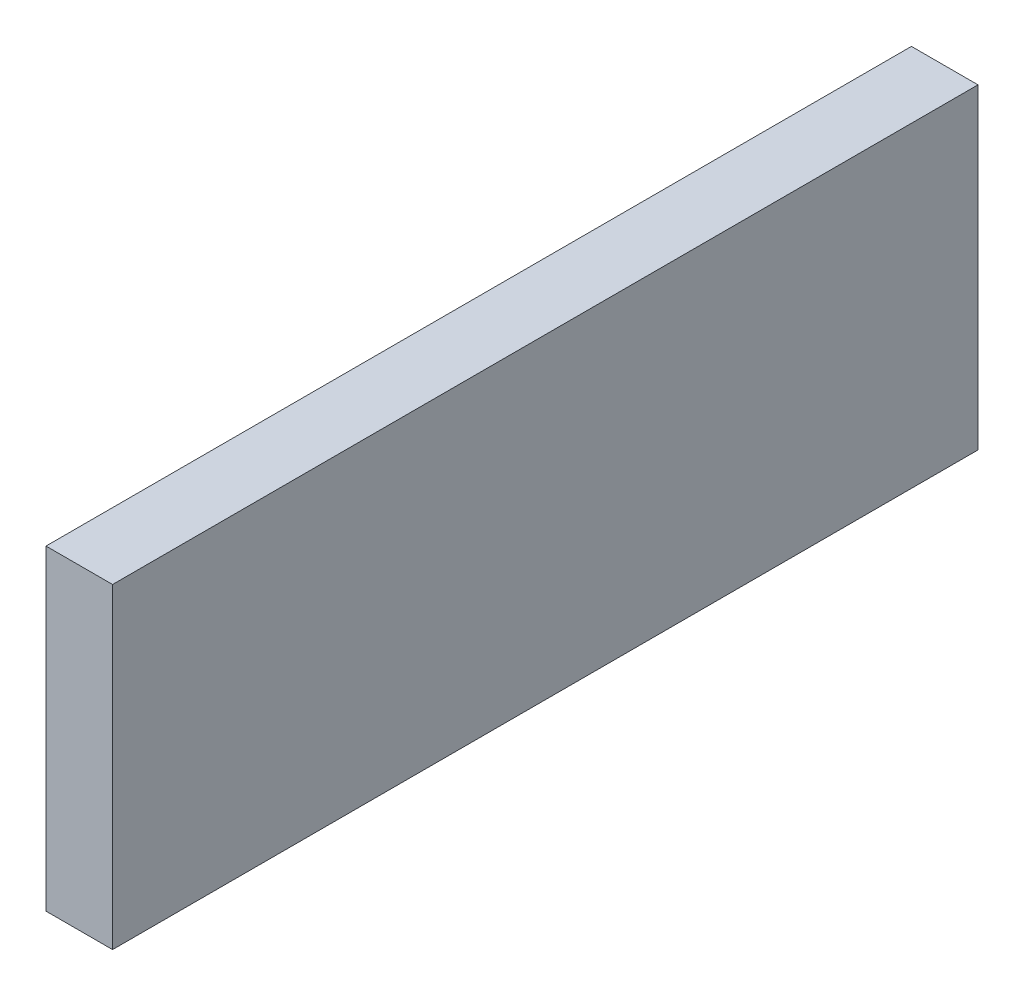
SolidWorks part; units mm, degrees
ref_plane "front" through (0, 0, 0) normal (0, 0, 1) x (1, 0, 0)
ref_plane "top" through (0, 0, 0) normal (0, 1, 0) x (1, 0, 0)
ref_plane "right" through (0, 0, 0) normal (1, 0, 0) x (0, 0, -1)
sketch "Sketch1" plane through (0, 0, 0) normal (0, 0, 1) x (1, 0, 0)
  line L1 (-12.7, 120.65) -> (12.7, 120.65)
  line L2 (-12.7, 120.65) -> (-12.7, 0)
  line L3 (-12.7, 0) -> (12.7, 0)
  line L4 (12.7, 120.65) -> (12.7, 0)
  dimension "D1" = 120.65
  dimension "D2" = 25.4
extrude "Extrude1" add sketch "Sketch1" against normal blind 330.2
